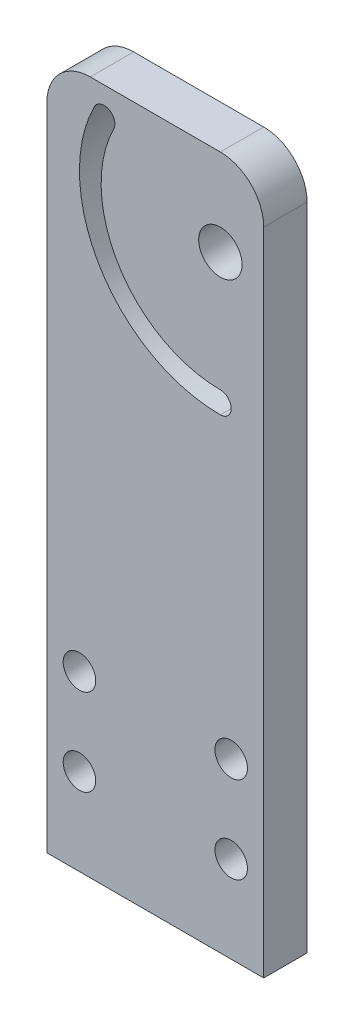
SolidWorks part; units mm, degrees
ref_plane "Front Plane" through (0, 0, 0) normal (0, 0, 1) x (1, 0, 0)
ref_plane "Top Plane" through (0, 0, 0) normal (0, 1, 0) x (1, 0, 0)
ref_plane "Right Plane" through (0, 0, 0) normal (1, 0, 0) x (0, 0, -1)
sketch "Sketch1" plane through (0, 0, 0) normal (0, 0, 1) x (1, 0, 0)
  line L0 (25.4, 88.9) -> (25.4, 0) construction
  line L1 (0, 0) -> (31.75, 0)
  line L2 (0, 0) -> (0, 101.6)
  line L3 (0, 101.6) -> (31.75, 101.6)
  line L4 (31.75, 0) -> (31.75, 101.6)
  line L5 (25.4, 88.9) -> (0, 101.6) construction
  circle A0 centre (25.4, 88.9) radius 3.175
  arc A1 (8.3612, 97.4194) -> (25.4, 69.85) centre (25.4, 88.9) ccw construction
  arc A2 (6.9413, 98.1294) -> (25.4, 68.2625) centre (25.4, 88.9) ccw
  arc A3 (9.7811, 96.7095) -> (25.4, 71.4375) centre (25.4, 88.9) ccw
  arc A4 (9.7811, 96.7095) -> (6.9413, 98.1294) centre (8.3612, 97.4194) ccw
  arc A5 (25.4, 68.2625) -> (25.4, 71.4375) centre (25.4, 69.85) ccw
  point P9 (9.1951, 78.8848)
  point P14 (0, 0)
  dimension "D3" = 6.35
  dimension "D6" = 19.05
  dimension "D7" = 3.175
  dimension "D1" = 101.6
  dimension "D2" = 31.75
  dimension "D4" = 12.7
  dimension "D5" = 6.35
extrude "Boss-Extrude1" add sketch "Sketch1" along normal blind 6.35
sketch "Sketch2" plane through (0, 0, 6.35) normal (0, 0, 1) x (1, 0, 0)
  line L0 (0, 101.6) -> (0, 0) construction
  line L2 (31.75, 0) -> (31.75, 101.6) construction
  line L3 (0, 0) -> (31.75, 0) construction
  circle A0 centre (4.7625, 25.4) radius 2.3813
  circle A1 centre (26.9875, 25.4) radius 2.3813
  circle A2 centre (4.7625, 12.7) radius 2.3813
  circle A3 centre (26.9875, 12.7) radius 2.3813
  point P14 (0, 0)
  point P15 (0, 0)
  dimension "D4" = 4.7625
  dimension "D5" = 4.7625
  dimension "D6" = 4.7625
  dimension "D7" = 4.7625
  dimension "D1" = 12.7
  dimension "D2" = 4.7625
  dimension "D3" = 4.7625
  dimension "D8" = 12.7
  dimension "D9" = 12.7
  dimension "D10" = 12.7
extrude "Cut-Extrude1" cut sketch "Sketch2" against normal through all
fillet "Fillet1" radius 6.35 2 edges at (0, 101.6, 3.175) (31.75, 101.6, 3.175)
